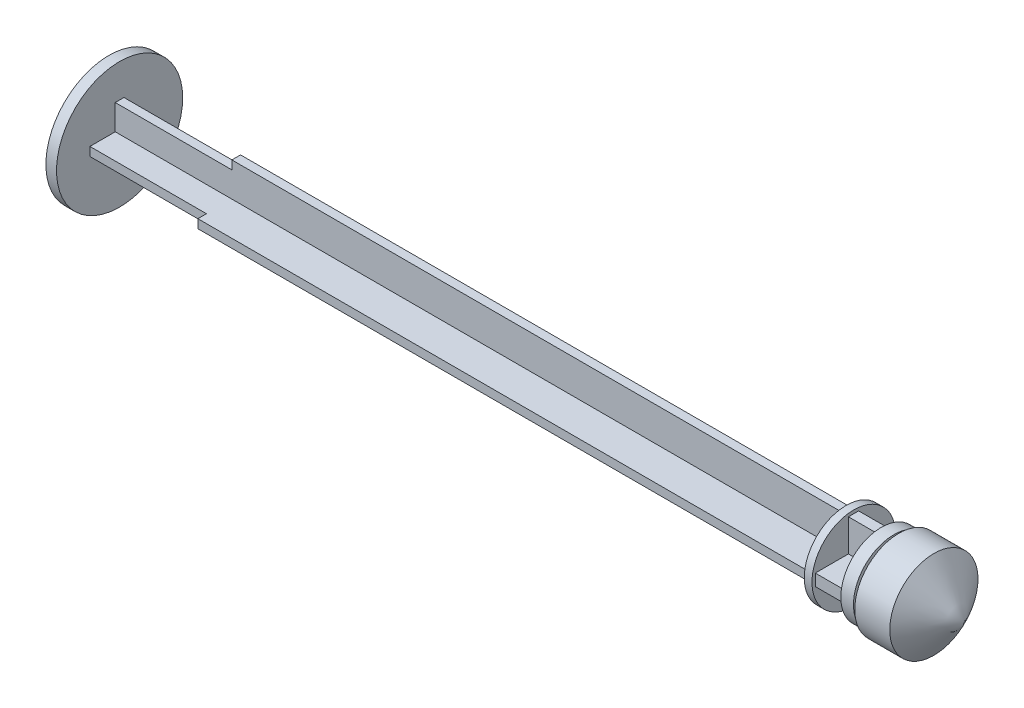
SolidWorks part; units mm, degrees
ref_plane "Front Plane" through (0, 0, 0) normal (0, 0, 1) x (1, 0, 0)
ref_plane "Top Plane" through (0, 0, 0) normal (0, 1, 0) x (1, 0, 0)
ref_plane "Right Plane" through (0, 0, 0) normal (1, 0, 0) x (0, 0, -1)
sketch "Sketch1" plane through (0, 0, 0) normal (1, 0, 0) x (0, 0, -1)
  circle A0 centre (0, 0) radius 6.235
  dimension "D1" = 12.47
extrude "Boss-Extrude1" add sketch "Sketch1" along normal blind 1.05
sketch "Sketch2" plane through (1.05, 0, 0) normal (1, 0, 0) x (0, 0, -1)
  line L1 (-2.935, -0.43) -> (2.935, -0.43)
  line L2 (-2.935, -0.43) -> (-2.935, 0.43)
  line L3 (-2.935, 0.43) -> (2.935, 0.43)
  line L4 (2.935, -0.43) -> (2.935, 0.43)
  line L5 (-0.43, 2.935) -> (0.43, 2.935)
  line L6 (-0.43, 2.935) -> (-0.43, -2.935)
  line L7 (-0.43, -2.935) -> (0.43, -2.935)
  line L8 (0.43, 2.935) -> (0.43, -2.935)
  dimension "D1" = 0.43
  dimension "D2" = 0.86
  dimension "D3" = 0.43
  dimension "D4" = 0.86
  dimension "D5" = 2.935
  dimension "D6" = 2.935
  dimension "D7" = 2.935
  dimension "D8" = 2.935
extrude "Boss-Extrude5" add sketch "Sketch2" along normal blind 11.52 contours L8 L5 L6 L3 | L8 L1 L6 L7
sketch "Sketch10" plane through (12.57, 0, 0) normal (1, 0, 0) x (0, 0, -1)
  line L0 (-0.43, 2.935) -> (-0.43, 0.43) construction
  line L1 (-0.43, 3.785) -> (0.43, 3.785)
  line L2 (-0.43, 3.785) -> (-0.43, -3.785)
  line L3 (-0.43, -3.785) -> (0.43, -3.785)
  line L4 (0.43, 3.785) -> (0.43, -3.785)
  line L5 (0.43, -0.43) -> (0.43, -2.935) construction
  dimension "D1" = 7.57
  dimension "D2" = 3.785
extrude "Boss-Extrude6" add sketch "Sketch10" along normal blind 60.27
sketch "Sketch11" plane through (12.57, 0, 0) normal (1, 0, 0) x (0, 0, -1)
  line L0 (-2.935, 0.43) -> (-0.43, 0.43) construction
  line L1 (-3.785, 0.43) -> (3.785, 0.43)
  line L2 (-3.785, 0.43) -> (-3.785, -0.43)
  line L3 (-3.785, -0.43) -> (3.785, -0.43)
  line L4 (3.785, 0.43) -> (3.785, -0.43)
  line L5 (0.43, -0.43) -> (2.935, -0.43) construction
  dimension "D1" = 7.57
  dimension "D2" = 3.785
extrude "Boss-Extrude8" add sketch "Sketch11" along normal blind 60.27
sketch "Sketch15" plane through (72.84, 0, 0) normal (1, 0, 0) x (0, 0, -1)
  circle A0 centre (0, 0) radius 4.13
extrude "Boss-Extrude9" add sketch "Sketch15" along normal blind 0.76
sketch "Sketch16" plane through (73.6, 0, 0) normal (1, 0, 0) x (0, 0, -1)
  line L1 (-0.5235, 3.8) -> (0.4868, 3.8)
  line L2 (-0.5235, 3.8) -> (-0.5235, -3.8)
  line L3 (-0.5235, -3.8) -> (0.4868, -3.8)
  line L4 (0.4868, 3.8) -> (0.4868, -3.8)
  line L5 (-3.8, 0.6246) -> (3.8, 0.6246)
  line L6 (-3.8, 0.6246) -> (-3.8, -0.5327)
  line L7 (-3.8, -0.5327) -> (3.8, -0.5327)
  line L8 (3.8, 0.6246) -> (3.8, -0.5327)
  dimension "D1" = 7.6
  dimension "D2" = 7.6
  dimension "D3" = 3.8
  dimension "D4" = 3.8
extrude "Boss-Extrude10" add sketch "Sketch16" along normal blind 2.71 contours L8 L5 L4 L7 | L2 L5 L4 L1
sketch "Sketch17" plane through (76.31, 0, 0) normal (1, 0, 0) x (0, 0, -1)
  circle A0 centre (0, 0) radius 3.99
extrude "Boss-Extrude11" add sketch "Sketch17" along normal blind 1.25
sketch "Sketch18" plane through (77.56, 0, 0) normal (1, 0, 0) x (0, 0, -1)
  line L1 (-0.45, 2.63) -> (0.45, 2.63)
  line L2 (-0.45, 2.63) -> (-0.45, -2.63)
  line L3 (-0.45, -2.63) -> (0.45, -2.63)
  line L4 (0.45, 2.63) -> (0.45, -2.63)
  line L5 (-2.63, 0.45) -> (2.63, 0.45)
  line L6 (-2.63, 0.45) -> (-2.63, -0.45)
  line L7 (-2.63, -0.45) -> (2.63, -0.45)
  line L8 (2.63, 0.45) -> (2.63, -0.45)
  dimension "D1" = 5.26
  dimension "D2" = 5.26
  dimension "D3" = 0.9
  dimension "D4" = 0.9
  dimension "D5" = 0.45
  dimension "D6" = 0.45
  dimension "D7" = 2.63
  dimension "D8" = 2.63
extrude "Boss-Extrude13" add sketch "Sketch18" along normal blind 0.5 contours L8 L5 L4 L7 | L2 L5 L4 L1 | L6 L7 L2 L5 | L2 L7 L4 L5 | L7 L2 L3 L4
sketch "Sketch19" plane through (78.06, 0, 0) normal (1, 0, 0) x (0, 0, -1)
  circle A0 centre (0, 0) radius 4.36
extrude "Boss-Extrude14" add sketch "Sketch19" along normal blind 3.46
sketch "Sketch20" plane through (81.52, 0, 0) normal (1, 0, 0) x (0, 0, -1)
  circle A0 centre (0, 0) radius 4.36
extrude "Boss-Extrude15" add sketch "Sketch20" along normal blind 3.46 draft 55
